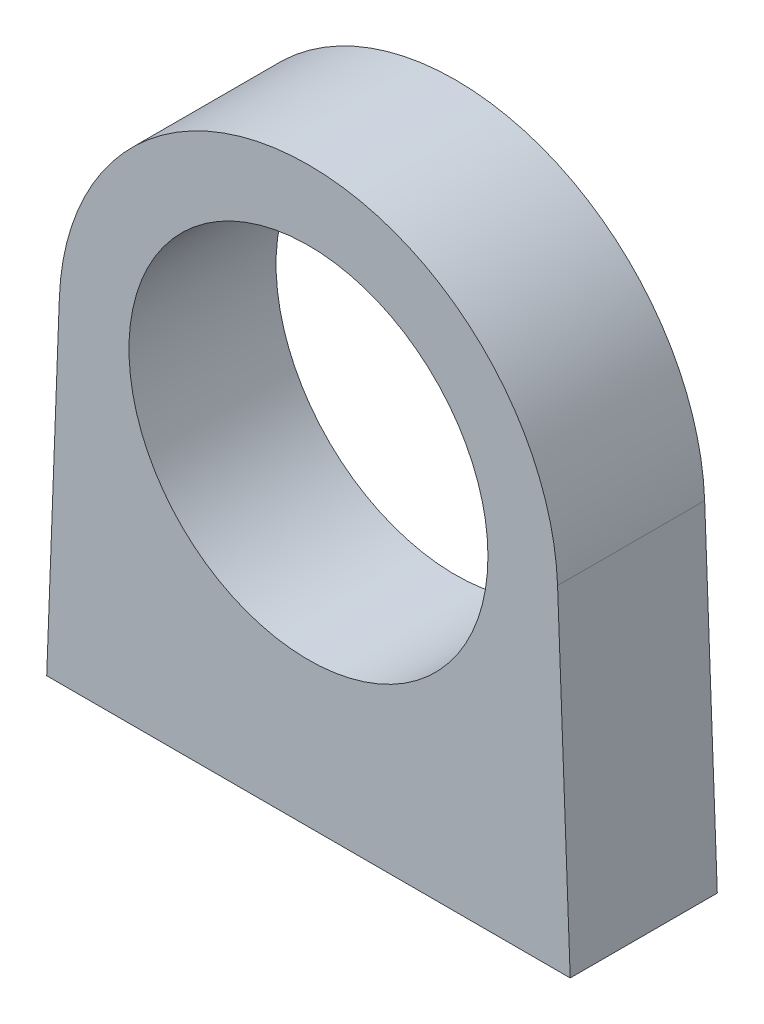
SolidWorks part; units mm, degrees
material "ABS PC"
ref_plane "Front Plane" through (0, 0, 0) normal (0, 0, 1) x (1, 0, 0)
ref_plane "Top Plane" through (0, 0, 0) normal (0, 1, 0) x (1, 0, 0)
ref_plane "Right Plane" through (0, 0, 0) normal (1, 0, 0) x (0, 0, -1)
sketch "Sketch1" plane through (0, 0, 0) normal (0, 0, 1) x (1, 0, 0)
  line L6 (0, -55) -> (0, 55) construction
  line L7 (-9.9928, 13.3788) -> (-10.5, 0)
  line L8 (55, 0) -> (-55, 0) construction
  line L9 (-10.5, 0) -> (10.5, 0)
  line L10 (10.5, 0) -> (9.9928, 13.3788)
  arc A1 (9.9928, 13.3788) -> (-9.9928, 13.3788) centre (0, 13) ccw
  circle A2 centre (0, 13) radius 7.2
other "Pen Sketch1" parameters "D2"=10.9435, "D3"=9.2262, "D1"=45.4944, "D4"=5.6397
extrude "Boss-Extrude1" add sketch "Sketch1" along normal mid plane 5.9
sketch "Sketch2" plane through (0, 0, 0) normal (0, -1, 0) x (1, 0, 0)
  line L0 (11.55, 0) -> (-11.55, 0) construction
  line L1 (-6.95, 0) -> (6.95, 0) construction
  line L2 (0, -3.245) -> (0, 3.245) construction
  circle A0 centre (-6.95, 0) radius 1.25
  circle A1 centre (6.95, 0) radius 1.25
  point P6 (0, 0)
  dimension "D1" = 2.5
  dimension "D2" = 13.9
extrude "Cut-Extrude1" cut sketch "Sketch2" against normal blind 5
